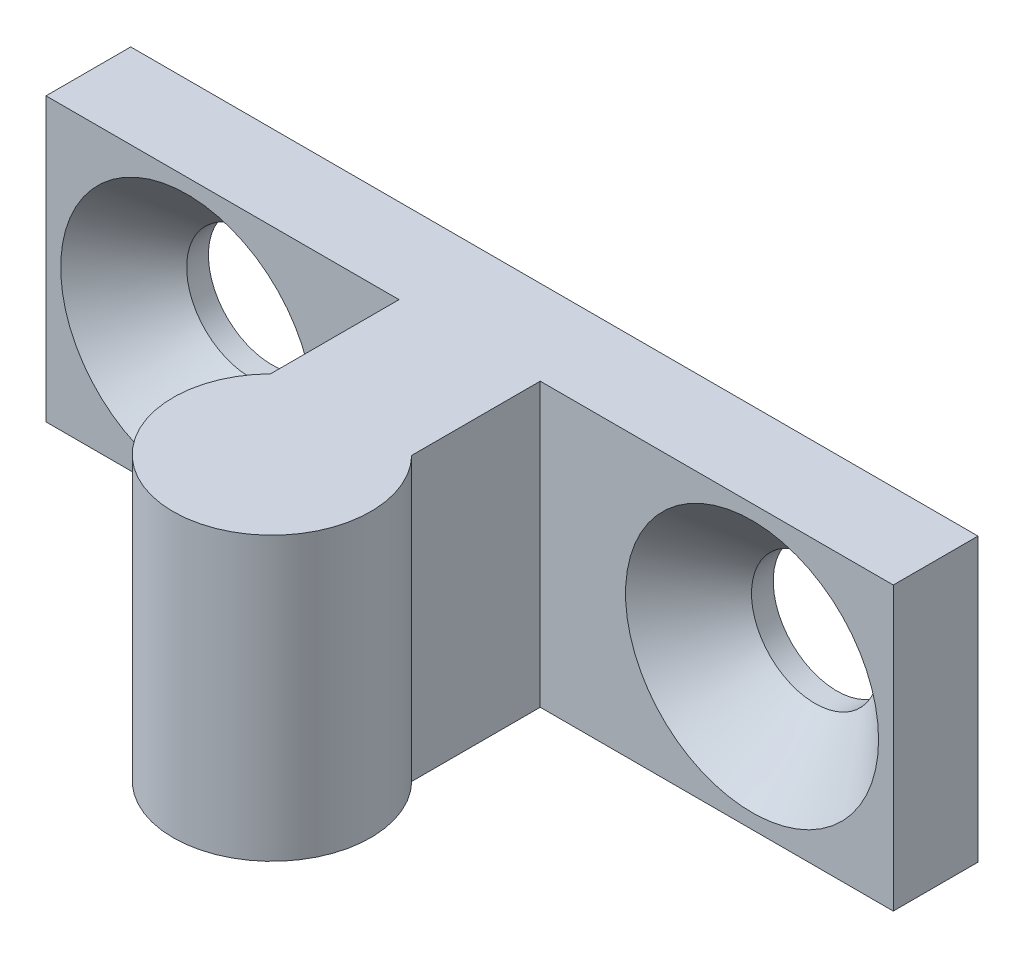
SolidWorks part; units mm, degrees
ref_plane "前视基准面" through (0, 0, 0) normal (0, 0, 1) x (1, 0, 0)
ref_plane "上视基准面" through (0, 0, 0) normal (0, 1, 0) x (1, 0, 0)
ref_plane "右视基准面" through (0, 0, 0) normal (1, 0, 0) x (0, 0, -1)
sketch "草图1" plane through (0, 0, 0) normal (0, 1, 0) x (1, 0, 0)
  line L1 (-15, 0) -> (15, 0)
  line L2 (-15, 0) -> (-15, -3)
  line L3 (-15, -3) -> (15, -3)
  line L4 (15, 0) -> (15, -3)
  line L5 (-2.5, -3) -> (2.5, -3)
  line L6 (-2.5, -3) -> (-2.5, -7.5505)
  line L8 (2.5, -3) -> (2.5, -7.5505)
  arc A0 (-2.5, -7.5505) -> (2.5, -7.5505) centre (0, -10) ccw
  point P4 (0, 0)
  dimension "D4" = 7
  dimension "D5" = 10
  dimension "D1" = 30
  dimension "D2" = 3
  dimension "D3" = 5
  dimension "D6" = 2.5
extrude "拉伸1" add sketch "草图1" along normal mid plane 10 contours L6 A0 L8 L3 | L4 L1 L2 L3
hole_wizard "M4 六角凹锥坑螺钉的锥形沉头孔1" positions "3D草图1" profile "草图2" countersink size "M4" standard "ISO" end condition through all
sketch3d "3D草图1"
  point P0 (-10, 0, 3)
  point P2 (10, 0, 3)
sketch "草图2" plane through (-10, 0, 3) normal (1, 0, 0) x (0, -1, 0)
  line L0 (0, 0) -> (0, 3)
  line L1 (0, 3) -> (2.25, 3)
  line L2 (2.25, 3) -> (2.25, 2.23)
  line L3 (2.25, 2.23) -> (4.48, 0)
  line L5 (4.48, 0) -> (0, 0)
  line L6 (-2.25, 2.23) -> (-4.48, 0) construction
  line L11 (0, -6.35) -> (0, 107.95) construction
  dimension "通孔孔直径" = 4.5
  dimension "通孔孔深度" = 3
  dimension "近端锥形沉头孔直径" = 8.96
  dimension "近端锥形沉头孔角度" = 90
